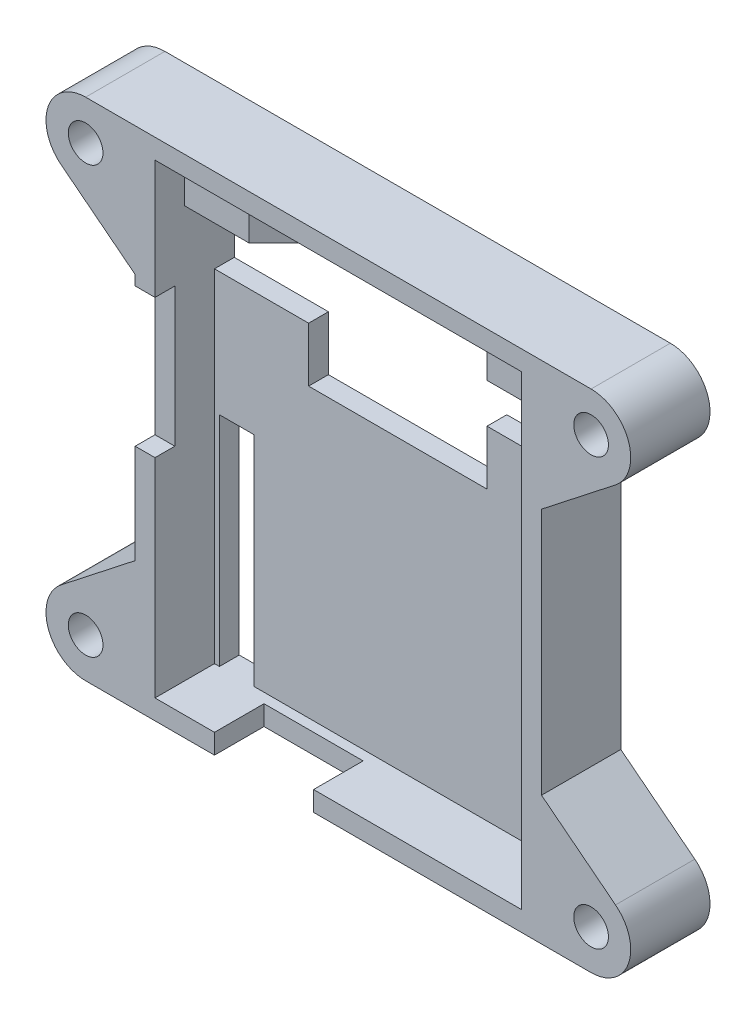
SolidWorks part; units mm, degrees
ref_plane "Front Plane" through (0, 0, 0) normal (0, 0, 1) x (1, 0, 0)
ref_plane "Top Plane" through (0, 0, 0) normal (0, 1, 0) x (1, 0, 0)
ref_plane "Right Plane" through (0, 0, 0) normal (1, 0, 0) x (0, 0, -1)
sketch "Sketch1" plane through (0, 0, 0) normal (0, 0, 1) x (1, 0, 0)
  line L1 (-20.5, 25.5) -> (20.5, 25.5)
  line L2 (-20.5, 25.5) -> (-20.5, -25.5)
  line L3 (-20.5, -25.5) -> (20.5, -25.5)
  line L4 (20.5, 25.5) -> (20.5, -25.5)
  line L5 (-20.5, 25.5) -> (20.5, -25.5) construction
  line L6 (-20.5, -25.5) -> (20.5, 25.5) construction
  point P0 (0, 0)
  dimension "D1" = 41
  dimension "D2" = 51
extrude "Boss-Extrude1" add sketch "Sketch1" along normal blind 8
shell "Shell1" thickness 2
sketch "Sketch2" plane through (0, 0, 2) normal (0, 0, 1) x (1, 0, 0)
  line L0 (18.5, -23.5) -> (18.5, 23.5) construction
  line L1 (-9, 23.5) -> (9, 23.5)
  line L2 (-9, 23.5) -> (-9, 18)
  line L3 (-9, 5.5) -> (9, 5.5)
  line L4 (9, 23.5) -> (9, 18)
  line L5 (-9, 23.5) -> (9, 5.5) construction
  line L6 (-9, 5.5) -> (9, 23.5) construction
  line L7 (-18.5, 18) -> (-9, 18)
  line L8 (-18.5, 18) -> (-18.5, 11)
  line L9 (-18.5, 11) -> (-9, 11)
  line L10 (18.5, 18) -> (18.5, 11)
  line L11 (-18.5, 18) -> (18.5, 11) construction
  line L12 (-18.5, 11) -> (18.5, 18) construction
  line L13 (0, 14.5) -> (0, 0) construction
  line L14 (18.5, 23.5) -> (-18.5, 23.5) construction
  line L15 (-9, 11) -> (-9, 5.5)
  line L16 (9, 18) -> (18.5, 18)
  line L17 (9, 11) -> (18.5, 11)
  line L18 (9, 11) -> (9, 5.5)
  line L19 (-9, 18) -> (9, 18) construction
  line L20 (9, 18) -> (9, 11) construction
  line L21 (9, 11) -> (-9, 11) construction
  line L22 (-9, 11) -> (-9, 18) construction
  point P0 (0, 14.5)
  point P5 (0, 14.5)
  dimension "D1" = 7
  dimension "D2" = 18
  dimension "D3" = 18
extrude "Cut-Extrude1" cut sketch "Sketch2" against normal through all
sketch "Sketch3" plane through (0, -25.5, 0) normal (0, -1, 0) x (1, 0, 0)
  line L0 (-20.5, 8) -> (20.5, 8) construction
  line L1 (-12.5, 8) -> (-2.5, 8)
  line L2 (-12.5, 8) -> (-12.5, 3)
  line L3 (-12.5, 3) -> (-2.5, 3)
  line L4 (-2.5, 8) -> (-2.5, 3)
  line L5 (-20.5, 8) -> (-20.5, 0) construction
  dimension "D1" = 5
  dimension "D2" = 8
  dimension "D3" = 10
extrude "Cut-Extrude2" cut sketch "Sketch3" against normal blind 7
sketch "Sketch4" plane through (-20.5, 0, 0) normal (-1, 0, 0) x (0, 0, 1)
  line L0 (8, 25.5) -> (8, -25.5) construction
  line L1 (8, 11.5) -> (6, 11.5)
  line L2 (8, 11.5) -> (8, -2.5)
  line L3 (8, -2.5) -> (6, -2.5)
  line L4 (6, 11.5) -> (6, -2.5)
  line L5 (8, 25.5) -> (0, 25.5) construction
  dimension "D1" = 14
  dimension "D2" = 14
  dimension "D3" = 2
extrude "Cut-Extrude3" cut sketch "Sketch4" against normal blind 7
sketch "Sketch5" plane through (0, 0, 0) normal (0, 0, -1) x (-1, 0, 0)
  line L0 (-14.5, -12.5) -> (14.5, -12.5) construction
  line L1 (-18, -1.5) -> (-14.5, -1.5)
  line L2 (-18, -1.5) -> (-18, -23.5)
  line L3 (-18, -23.5) -> (-14.5, -23.5)
  line L4 (-14.5, -1.5) -> (-14.5, -23.5)
  line L5 (14.5, -1.5) -> (18, -1.5)
  line L6 (14.5, -1.5) -> (14.5, -23.5)
  line L7 (14.5, -23.5) -> (18, -23.5)
  line L8 (18, -1.5) -> (18, -23.5)
  line L9 (20.5, -25.5) -> (-20.5, -25.5) construction
  line L11 (0, -12.5) -> (0, 0) construction
  line L12 (-14.5, -1.5) -> (14.5, -1.5) construction
  dimension "D1" = 29
  dimension "D2" = 3.5
  dimension "D3" = 3.5
  dimension "D4" = 2
  dimension "D5" = 22
extrude "Cut-Extrude4" cut sketch "Sketch5" against normal blind 7
sketch "Sketch6" plane through (0, 0, 0) normal (0, 0, 1) x (1, 0, 0)
  line L0 (25.5, 25.5) -> (20.5, 25.5)
  line L1 (20.5, 25.5) -> (20.5, 12.5)
  line L2 (20.5, -25.5) -> (20.5, 25.5) construction
  line L3 (20.5, 12.5) -> (27.9672, 18.3515)
  arc A0 (27.9672, 18.3515) -> (25.5, 25.5) centre (25.5, 21.5) ccw
  circle A1 centre (25.5, 21.5) radius 1.75
  dimension "D1" = 8
  dimension "D4" = 3.5
  dimension "D2" = 13
  dimension "D3" = 5
extrude "Boss-Extrude2" add sketch "Sketch6" along normal blind 8
mirror "Mirror1" about plane through (0, 0, 0) normal (1, 0, 0) of "Boss-Extrude2" second plane through (0, 0, 0) second plane normal (0, 1, 0)
sketch "Sketch7" plane through (0, 0, 2) normal (0, 0, 1) x (1, 0, 0)
  line L4 (-9, 18) -> (-9, 23.5)
  line L5 (-9, 23.5) -> (-18.5, 23.5)
  line L6 (-18.5, 23.5) -> (-18.5, 18)
  line L7 (-18.5, 18) -> (-9, 18)
  line L8 (-9, 18) -> (-9, 23.5)
  line L9 (-9, 23.5) -> (-18.5, 23.5)
  line L10 (-18.5, 23.5) -> (-18.5, 18)
  line L11 (-18.5, 18) -> (-9, 18)
  line L12 (9, 18) -> (18.5, 18)
  line L13 (18.5, 18) -> (18.5, 23.5)
  line L14 (18.5, 23.5) -> (9, 23.5)
  line L15 (9, 23.5) -> (9, 18)
  line L16 (9, 18) -> (18.5, 18)
  line L17 (18.5, 18) -> (18.5, 23.5)
  line L18 (18.5, 23.5) -> (9, 23.5)
  line L19 (9, 23.5) -> (9, 18)
  dimension "D1" = 0
  dimension "D2" = 0
extrude "Boss-Extrude3" add sketch "Sketch7" along normal blind 3
chamfer "Chamfer1" distance 3 angle 45 2 edges at (9, 20.75, 5) (-9, 20.75, 5)
